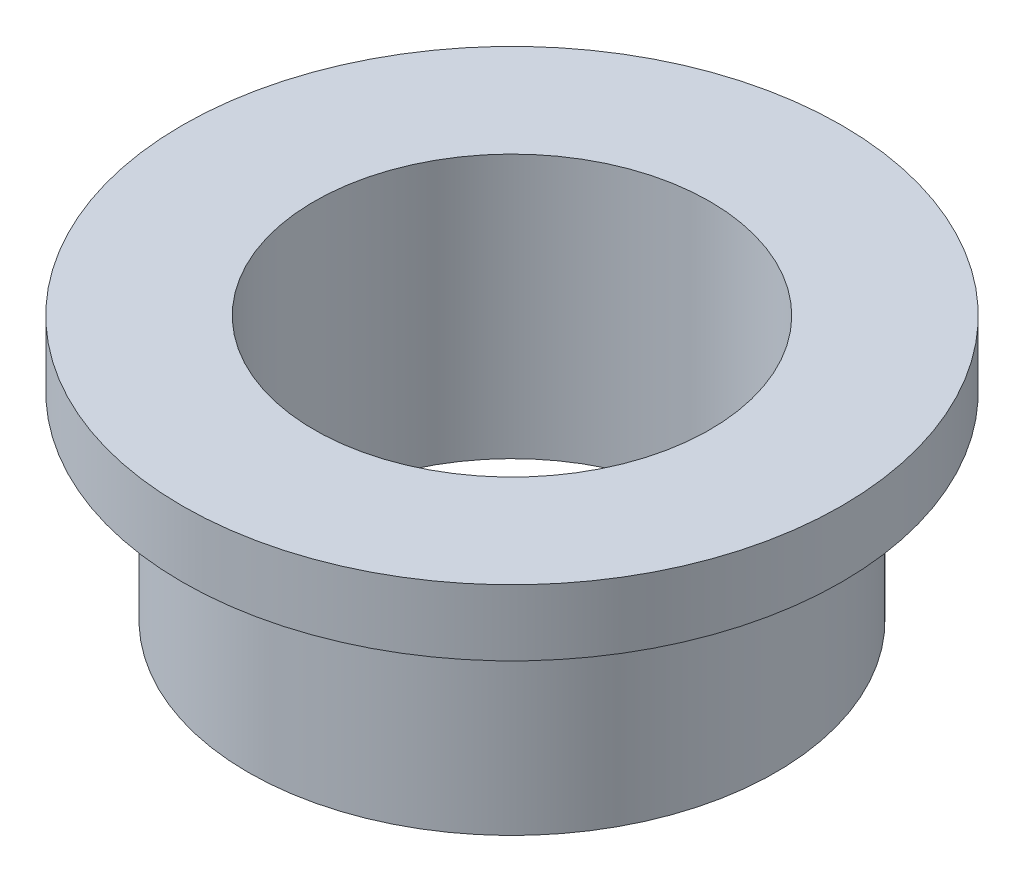
SolidWorks part; units mm, degrees
material "铜"
ref_plane "前视基准面" through (0, 0, 0) normal (0, 0, 1) x (1, 0, 0)
ref_plane "上视基准面" through (0, 0, 0) normal (0, 1, 0) x (1, 0, 0)
ref_plane "右视基准面" through (0, 0, 0) normal (1, 0, 0) x (0, 0, -1)
sketch "草图1" plane through (0, 0, 0) normal (1, 0, 0) x (0, 0, -1)
  line L0 (0, 0) -> (0, 9.3871) construction
  line L1 (3, 4) -> (3, 0)
  line L2 (3, 0) -> (4, 0)
  line L3 (4, 0) -> (4, 3)
  line L4 (4, 3) -> (5, 3)
  line L5 (5, 3) -> (5, 4)
  line L6 (5, 4) -> (3, 4)
  dimension "D1" = 1
  dimension "D2" = 4
  dimension "D3" = 1
  dimension "D4" = 2
  dimension "D5" = 3
revolve "旋转1" add sketch "草图1" angle 360 about L0
